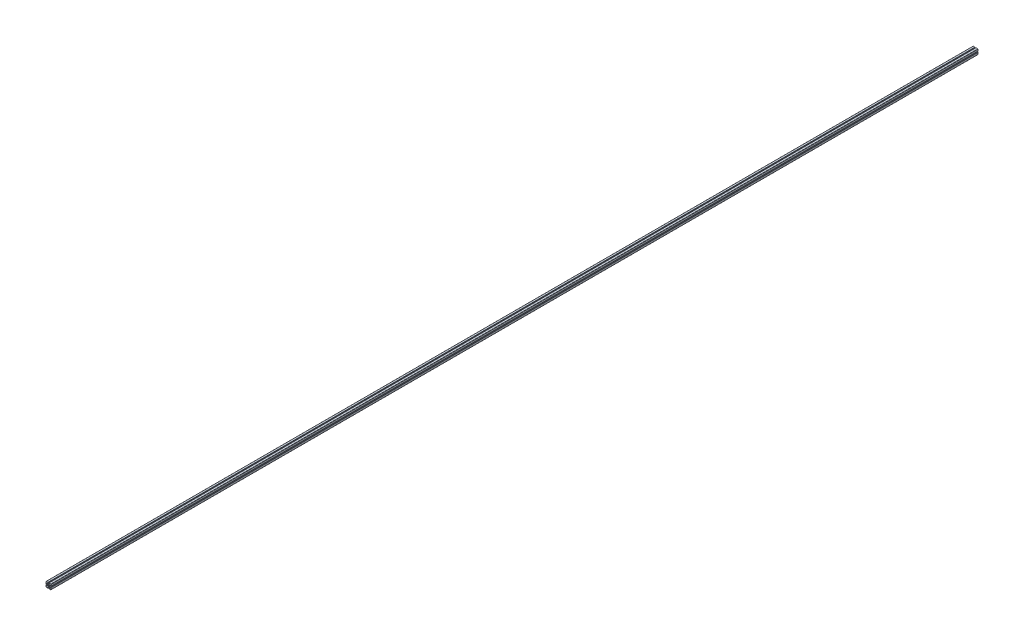
SolidWorks part; units mm, degrees
ref_plane "Front" through (0, 0, 0) normal (0, 0, 1) x (1, 0, 0)
ref_plane "Top" through (0, 0, 0) normal (0, 1, 0) x (1, 0, 0)
ref_plane "Right" through (0, 0, 0) normal (1, 0, 0) x (0, 0, -1)
sketch "草图1" plane through (0, 0, 0) normal (0, 0, 1) x (1, 0, 0)
  line L1 (-20, 20) -> (20, 20)
  line L2 (-20, 20) -> (-20, -20)
  line L3 (-20, -20) -> (20, -20)
  line L4 (20, 20) -> (20, -20)
  line L5 (-20, 20) -> (20, -20) construction
  line L6 (-20, -20) -> (20, 20) construction
  point P0 (0, 0)
  dimension "D1" = 40
extrude "凸台-拉伸1" add sketch "草图1" along normal blind 7420
sketch "草图2" plane through (0, 0, 7420) normal (0, 0, 1) x (1, 0, 0)
  circle A0 centre (0, 0) radius 4.05
  dimension "D1" = 8.1
extrude "切除-拉伸1" cut sketch "草图2" against normal blind 10000
sketch "草图4" plane through (0, 0, 7420) normal (0, 0, 1) x (1, 0, 0)
  line L0 (20, -20) -> (20, 20) construction
  line L1 (20, 0) -> (20, 4)
  line L2 (20, 0) -> (20, -2.652)
  line L3 (7.8769, 2.6) -> (7.8769, -2.6)
  line L4 (20, 4) -> (16, 4)
  line L5 (20, -2.652) -> (16, -2.652)
  line L6 (16, 10.5) -> (16, 4)
  line L7 (16, 10.5) -> (7.8769, 2.6)
  line L8 (16, -10.5) -> (7.8769, -2.6)
  line L9 (16, -2.652) -> (16, -10.5)
  point P11 (7.8769, 0)
  point P12 (16, 0)
extrude "切除-拉伸2" cut sketch "草图4" against normal blind 10000
fillet "圆角1" radius 1 8 edges at (16, 10.5, 3710) (16, -10.5, 3710) (7.8769, 2.6, 3710) (20, -2.652, 3710) (16, -2.652, 3710) (20, 4, 3710) (16, 4, 3710) (7.8769, -2.6, 3710)
pattern_circular "阵列(圆周)2" count 4 over 360 about axis through (0, 0, 0) along (0, 0, 1) of "切除-拉伸2"
fillet "圆角2" radius 1 8 edges at (10.5, 16, 3710) (-10.5, 16, 3710) (-4, 20, 3710) (2.652, 16, 3710) (2.652, 20, 3710) (-2.6, 7.8769, 3710) (-4, 16, 3710) (2.6, 7.8769, 3710)
fillet "圆角3" radius 1 8 edges at (-7.8769, -2.6, 3710) (-7.8769, 2.6, 3710) (-20, 2.652, 3710) (-16, 10.5, 3710) (-20, -4, 3710) (-16, -4, 3710) (-16, -10.5, 3710) (-16, 2.652, 3710)
fillet "圆角4" radius 1 8 edges at (4, -20, 3710) (4, -16, 3710) (10.5, -16, 3710) (-2.652, -20, 3710) (2.6, -7.8769, 3710) (-2.6, -7.8769, 3710) (-2.652, -16, 3710) (-10.5, -16, 3710)
fillet "圆角5" radius 2 4 edges at (-20, -20, 3710) (20, -20, 3710) (-20, 20, 3710) (20, 20, 3710)
